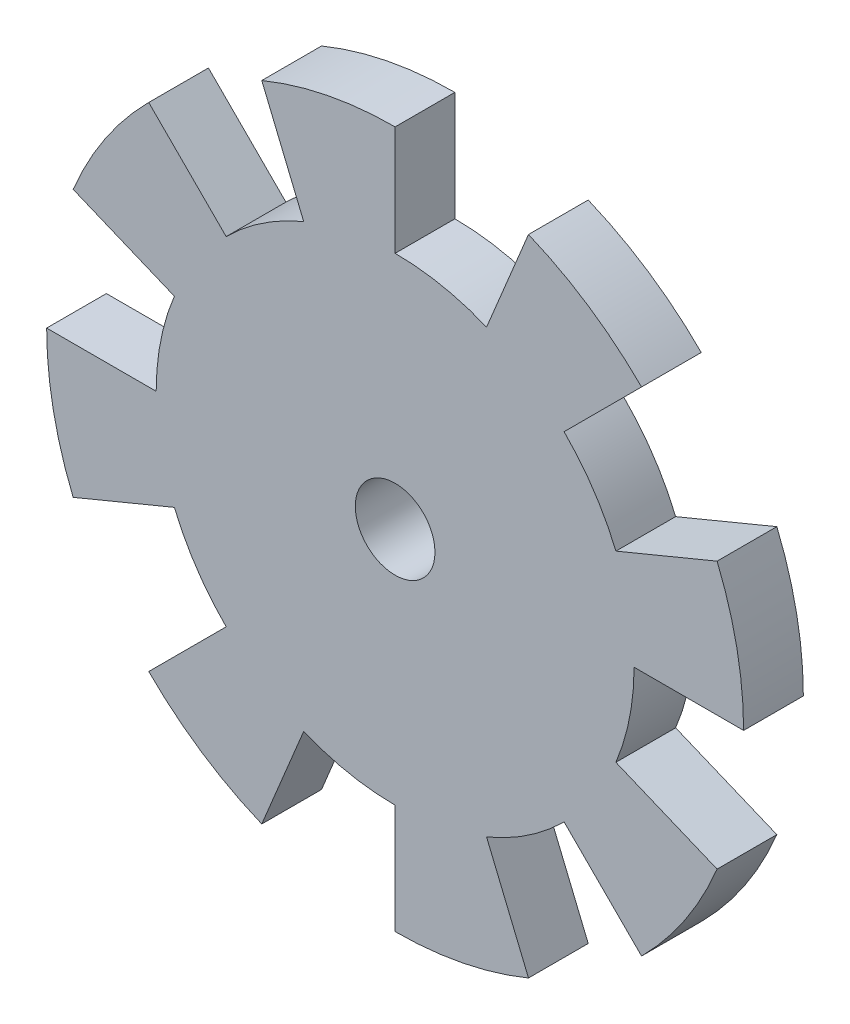
SolidWorks part; units mm, degrees
ref_plane "Front Plane" through (0, 0, 0) normal (0, 0, 1) x (1, 0, 0)
ref_plane "Top Plane" through (0, 0, 0) normal (0, 1, 0) x (1, 0, 0)
ref_plane "Right Plane" through (0, 0, 0) normal (1, 0, 0) x (0, 0, -1)
sketch "Sketch1" plane through (0, 0, 0) normal (0, 0, 1) x (1, 0, 0)
  line L0 (0, 24) -> (0, 35)
  line L1 (9.1844, 22.1731) -> (13.3939, 32.3358)
  line L2 (16.9706, 16.9706) -> (24.7487, 24.7487)
  line L3 (22.1731, 9.1844) -> (32.3358, 13.3939)
  line L4 (24, 0) -> (35, 0)
  line L5 (22.1731, -9.1844) -> (32.3358, -13.3939)
  line L6 (16.9706, -16.9706) -> (24.7487, -24.7487)
  line L7 (9.1844, -22.1731) -> (13.3939, -32.3358)
  line L8 (0, -24) -> (0, -35)
  line L9 (-9.1844, -22.1731) -> (-13.3939, -32.3358)
  line L10 (-16.9706, -16.9706) -> (-24.7487, -24.7487)
  line L11 (-22.1731, -9.1844) -> (-32.3358, -13.3939)
  line L12 (-24, 0) -> (-35, 0)
  line L13 (-22.1731, 9.1844) -> (-32.3358, 13.3939)
  line L14 (-16.9706, 16.9706) -> (-24.7487, 24.7487)
  line L15 (-9.1844, 22.1731) -> (-13.3939, 32.3358)
  circle A0 centre (0, 0) radius 4
  circle A1 centre (0, 0) radius 24
  circle A2 centre (0, 0) radius 35
  point P40 (0, 0)
  point P48 (0, 0)
  dimension "D1" = 8
  dimension "D2" = 48
  dimension "D3" = 70
  dimension "D4" = 11
  dimension "D5" = 16
extrude "Boss-Extrude1" add sketch "Sketch1" along normal blind 6
